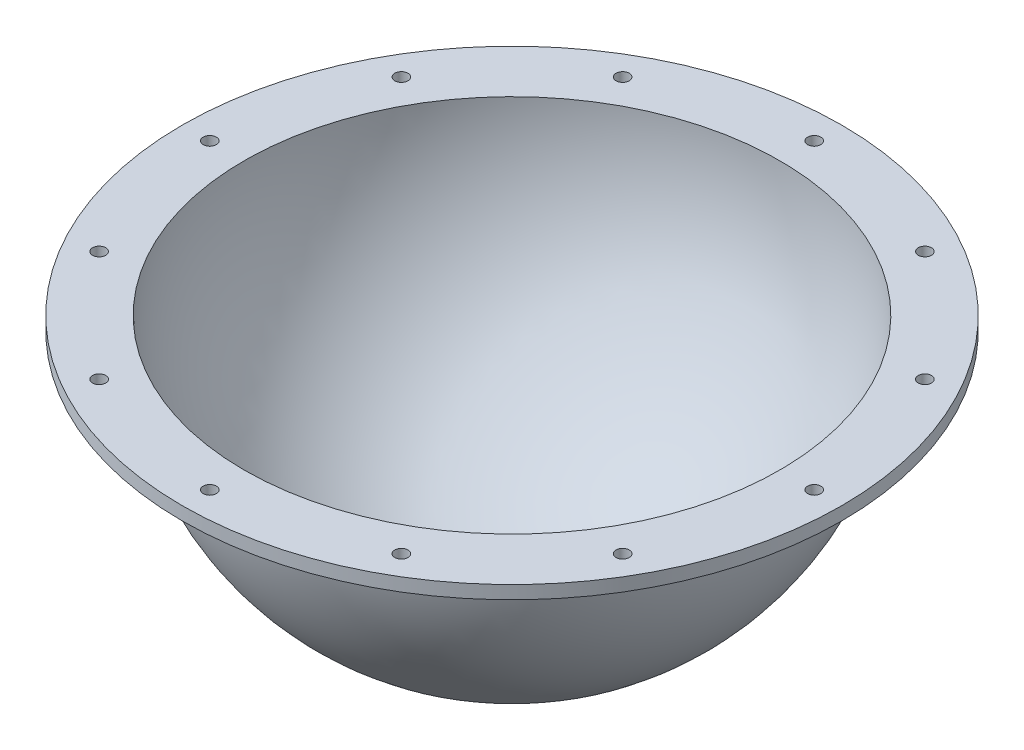
SolidWorks part; units mm, degrees
material "AISI 1020 Steel, Cold Rolled"
ref_plane "Front Plane" through (0, 0, 0) normal (0, 0, 1) x (1, 0, 0)
ref_plane "Top Plane" through (0, 0, 0) normal (0, 1, 0) x (1, 0, 0)
ref_plane "Right Plane" through (0, 0, 0) normal (1, 0, 0) x (0, 0, -1)
sketch "Sketch1" plane through (0, 0, 0) normal (0, 1, 0) x (1, 0, 0)
  line L0 (0, 250) -> (0, 243.75)
  line L1 (0, -243.75) -> (0, -250)
  line L2 (0, 250) -> (0, -250) construction
  arc A0 (0, 250) -> (0, -250) centre (0, 0) ccw
  arc A1 (0, 243.75) -> (0, -243.75) centre (0, 0) ccw
  dimension "D1" = 500
  dimension "D2" = 6.25
revolve "Revolve1" add sketch "Sketch1" angle 180 about L2
ref_axis "Axis1" through (0, 0, 0) along (0, 1, 0)
sketch "Sketch3" plane through (0, 0, 0) normal (1, 0, 0) x (0, 0, -1)
  line L0 (-250, 0) -> (-300, 0)
  line L1 (-300, 0) -> (-300, -12)
  line L2 (-300, -12) -> (-249.7118, -12)
  line L3 (-300, 0) -> (300, 0) construction
  arc A0 (-250, 0) -> (250, 0) centre (0, 0) ccw construction
  arc A1 (-250, 0) -> (-249.7118, -12) centre (0, 0) ccw
  dimension "D1" = 600
  dimension "D2" = 12
revolve "Revolve2" add sketch "Sketch3" angle 360 about axis through (0, 0, 0) along (0, 1, 0)
sketch "Sketch10" plane through (0, 0, 0) normal (0, 1, 0) x (1, 0, 0)
  circle A0 centre (0, 0) radius 275 construction
  circle A1 centre (0, 275) radius 6
  circle A2 centre (-137.5, 238.157) radius 6
  circle A3 centre (-238.157, 137.5) radius 6
  circle A4 centre (-275, 0) radius 6
  circle A5 centre (-238.157, -137.5) radius 6
  circle A6 centre (-137.5, -238.157) radius 6
  circle A7 centre (0, -275) radius 6
  circle A8 centre (137.5, -238.157) radius 6
  circle A9 centre (238.157, -137.5) radius 6
  circle A10 centre (275, 0) radius 6
  circle A11 centre (238.157, 137.5) radius 6
  circle A12 centre (137.5, 238.157) radius 6
  point P30 (0, 0)
  dimension "D2" = 12
  dimension "D1" = 550
  dimension "D3" = 12
extrude "Cut-Extrude1" cut sketch "Sketch10" against normal through all
equation "\"mbtOD\" = 850"
equation "\"mbtT\" = 6"
equation "\"mbtL\" = 1500"
equation "\"mbtFlangeOD\" = 950"
equation "\"mbtFlangeT\" = 12"
equation "\"mbtFlangeBoltCircleDia\" = 650"
equation "\"mbtFlangeHoleDia\" = 12"
equation "\"mbtOringSize\" = 10 "
equation "\"mbtOringDia\" = 620"
equation "\"mbtWidth\" = 2250"
equation "\"skiWidth\" = 1250"
equation "\"mbtCapL\" = 500"
equation "\"vbtRearOD\" = 500"
equation "\"vbtRearT\" = 6.25"
equation "\"vbtRearFlangeOD\" = 600"
equation "\"vbtRearFlangeT\" = 12"
equation "\"vbtRearBoltHoleDia\" = 12"
equation "\"D1@Sketch1\"=\"vbtRearOD\""
equation "\"D2@Sketch1\"=\"vbtRearT\""
equation "\"D1@Sketch3\"=\"vbtRearFlangeOD\""
equation "\"D2@Sketch3\"=\"vbtRearFlangeT\""
equation "\"D1@Sketch10\"=(\"vbtRearOD\"+\"vbtRearFlangeOD\")/2"
equation "\"D2@Sketch10\"=\"vbtRearBoltHoleDia\""
